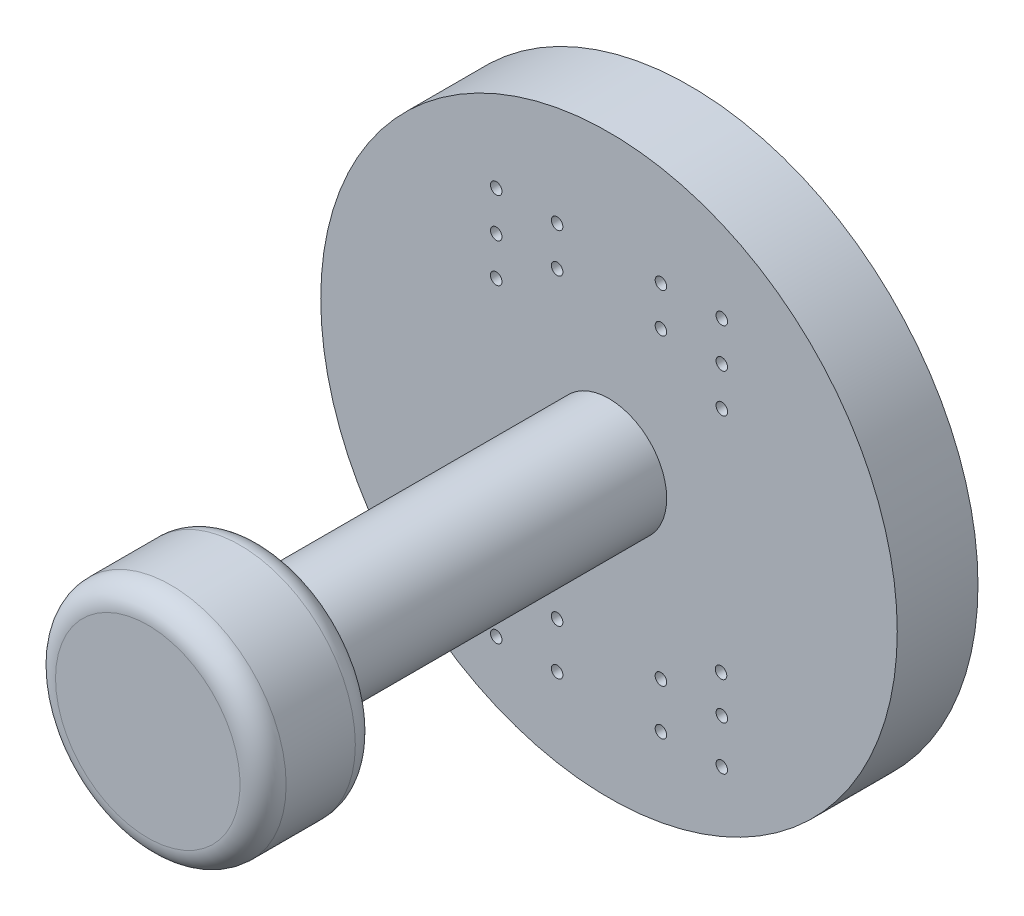
SolidWorks part; units mm, degrees
ref_plane "Front Plane" through (0, 0, 0) normal (0, 0, 1) x (1, 0, 0)
ref_plane "Top Plane" through (0, 0, 0) normal (0, 1, 0) x (1, 0, 0)
ref_plane "Right Plane" through (0, 0, 0) normal (1, 0, 0) x (0, 0, -1)
sketch "Sketch1" plane through (0, 0, 0) normal (0, 0, 1) x (1, 0, 0)
  circle A0 centre (0, 0) radius 25
  dimension "D1" = 50
extrude "Boss-Extrude1" add sketch "Sketch1" along normal blind 5
sketch "Sketch2" plane through (0, 0, 0) normal (0, 0, -1) x (-1, 0, 0)
  line L0 (0, 0) -> (0, 25) construction
  line L1 (0, 0) -> (0, -25) construction
  line L2 (-11.9711, -0.8326) -> (-14.1368, 0.4162)
  line L3 (-14.1368, 0.4162) -> (-15.5696, 8.7946)
  line L4 (-14.9974, 9.9289) -> (-9.0807, 6.1881)
  line L5 (-9.0807, 6.1881) -> (-9.0807, 4.1881)
  line L6 (0, 0) -> (-6.2363, 1.8326)
  line L7 (0.7585, 1.8326) -> (-0.7585, 1.8326)
  line L8 (-0.7585, 1.8326) -> (-0.7585, 2.3934)
  line L9 (0.7585, 1.8326) -> (0.7585, 2.3934)
  line L10 (0, 0) -> (6.2363, 1.8326)
  line L11 (11.9711, -0.8326) -> (14.1368, 0.4162)
  line L12 (9.0807, 6.1881) -> (9.0807, 4.1881)
  line L13 (14.9974, 9.9289) -> (9.0807, 6.1881)
  line L14 (14.1368, 0.4162) -> (15.5696, 8.7946)
  circle A0 centre (0, 0) radius 25 construction
  arc A1 (-11.9711, -0.8326) -> (11.9711, -0.8326) centre (0, 0) ccw
  arc A2 (-9.0807, 4.1881) -> (0, 10) centre (0, 0) cw
  arc A3 (-15.5696, 8.7946) -> (-14.9974, 9.9289) centre (-16.9766, 10.216) cw
  arc A4 (-6.2363, 1.8326) -> (6.2363, 1.8326) centre (0, -2.7478) ccw
  arc A5 (-0.7585, 2.3934) -> (0.7585, 2.3934) centre (0, 4.1881) cw
  circle A6 centre (-0.8787, 4.4971) radius 0.5181
  circle A7 centre (0.8787, 4.4971) radius 0.5181
  arc A8 (9.0807, 4.1881) -> (0, 10) centre (0, 0) ccw
  arc A9 (15.5696, 8.7946) -> (14.9974, 9.9289) centre (16.9766, 10.216) ccw
  ellipse E0 centre (-3.1163, -3.2887) end of major axis (-3.1163, -5.3887) minor radius 1.5
  ellipse E1 centre (3.1163, -3.2887) end of major axis (3.1163, -5.3887) minor radius 1.5
  point P16 (-5.3907, 8.4226)
  point P32 (-0.8806, 2.3934)
  point P33 (-0.7585, 2.3934)
  point P35 (0, 1.8326)
  point P49 (0, 6.1365)
  point P50 (0, 0)
  dimension "D1" = 12
  dimension "D2" = 10
  dimension "D7" = 2
  dimension "D10" = 9.704
  dimension "D14" = 16.9766
  dimension "D21" = 7.7377
  dimension "D25" = 1.9484
  dimension "D26" = 1.0363
  dimension "D27" = 0.8787
  dimension "D28" = 1.0363
  dimension "D29" = 1.0363
  dimension "D30" = 0.8787
  dimension "D31" = 0.8787
  dimension "D32" = 1.8601
  dimension "D3" = 7
  dimension "D4" = 8.5
  dimension "D5" = 2.5
  dimension "D6" = 2
  dimension "D8" = 230.327
  dimension "D9" = 237.697
  dimension "D11" = 57.697
  dimension "D12" = 9.0807
  dimension "D13" = 9.704
  dimension "D15" = 6.5
  dimension "D16" = 3
  dimension "D17" = 4.2
  dimension "D18" = 4.6163
  dimension "D19" = 3.1163
  dimension "D20" = 6.2363
  dimension "D22" = 6.0487
  dimension "D23" = 0.5608
  dimension "D24" = 0.7585
extrude "Boss-Extrude2" add sketch "Sketch2" along normal blind 2 contours L14 A9 L13 L12 A8 A2 L5 L4 A3 L3 L2 A1 L11 L8 A5 L9 L7 A4 L6 L10 | E0 | E1 | A7 | A6
sketch "Sketch3" plane through (0, 0, 0) normal (0, 0, -1) x (-1, 0, 0)
  line L0 (0, 0) -> (0, 25) construction
  line L1 (0, 0) -> (0, -25) construction
  circle A1 centre (0, 0) radius 25 construction
  circle A4 centre (-4.5014, 15.9102) radius 0.5
  circle A5 centre (-4.5014, 12.4971) radius 0.5
  circle A6 centre (-4.5014, -13.81) radius 0.5
  circle A7 centre (-4.5014, -17.7681) radius 0.5
  circle A10 centre (-9.7824, 15.9102) radius 0.5
  circle A11 centre (-9.7824, 12.4971) radius 0.5
  circle A12 centre (-9.7824, 9.1314) radius 0.5
  circle A13 centre (-9.7137, -10.705) radius 0.5
  circle A14 centre (-9.7837, -13.927) radius 0.5
  circle A15 centre (-9.7824, -17.7681) radius 0.5
  circle A17 centre (0, 0) radius 23.3549
  circle A18 centre (4.5014, -13.81) radius 0.5
  circle A19 centre (4.5014, -17.7681) radius 0.5
  circle A20 centre (9.7824, -17.7681) radius 0.5
  circle A21 centre (9.7837, -13.927) radius 0.5
  circle A22 centre (9.7137, -10.705) radius 0.5
  circle A23 centre (4.5014, 15.9102) radius 0.5
  circle A24 centre (4.5014, 12.4971) radius 0.5
  circle A25 centre (9.7824, 9.1314) radius 0.5
  circle A26 centre (9.7824, 12.4971) radius 0.5
  circle A27 centre (9.7824, 15.9102) radius 0.5
  point P5 (0, 0)
  point P8 (0, 0)
  point P9 (0, 0)
  point P10 (-9.7824, -10.6406)
  point P19 (0, 0)
  point P20 (0, 0)
  point P21 (-9.7837, -10.705)
  point P22 (0, 0)
  point P35 (0, 0)
  point P36 (0, 0)
  point P58 (0, 0)
  dimension "D1" = 1
  dimension "D2" = 1
  dimension "D3" = 1
  dimension "D4" = 1
  dimension "D5" = 1
  dimension "D6" = 1
  dimension "D7" = 1
  dimension "D8" = 1
  dimension "D9" = 1
  dimension "D10" = 1
  dimension "D11" = 9.7824
  dimension "D12" = 3.4132
  dimension "D13" = 9.7837
  dimension "D17" = 17.0201
  dimension "D19" = 23.3549
  dimension "D20" = 1
  dimension "D21" = 18.3294
  dimension "D22" = 20.283
  dimension "D23" = 9.7137
  dimension "D25" = 4.5014
  dimension "D26" = 13.2831
  dimension "D28" = 18.677
  dimension "D14" = 9.7824
  dimension "D15" = 4.5014
  dimension "D16" = 4.5014
  dimension "D18" = 14.5251
  dimension "D24" = 14.4552
  dimension "D27" = 4.5014
  dimension "D29" = 9.7824
  dimension "D30" = 19.5648
  dimension "D31" = 13.382
  dimension "D32" = 16.5348
extrude "Cut-Extrude1" cut sketch "Sketch3" against normal through all contours A26 | A27 | A25 | A24 | A23 | A20 | A21 | A22 | A19 | A18 | A4 | A5 | A11 | A10 | A12 | A7 | A6 | A14 | A13 | A15
sketch "Sketch4" plane through (0, 0, 0) normal (0, 0, -1) x (-1, 0, 0)
  circle A0 centre (0, 0) radius 23.0074
  circle M19 centre (0, 0) radius 25
  dimension "D1" = 46.0148
extrude "Boss-Extrude4" add sketch "Sketch4" along normal blind 2 contours A0 M19
sketch "Sketch5" plane through (0, 0, 0) normal (1, 0, 0) x (0, 0, -1)
  line L0 (0, 0) -> (-17.0912, 0) construction
  line L1 (-5, 5) -> (-35, 5)
  line L2 (-5, 25) -> (-5, -25) construction
  line L3 (-35, 5) -> (-35, 8)
  line L4 (-37, 10) -> (-43, 10)
  line L5 (-45, 8) -> (-45, 0)
  line L6 (-5, 0) -> (-45, 0)
  line L7 (-5, 5) -> (-5, 0)
  arc A0 (-43, 10) -> (-45, 8) centre (-43, 8) ccw
  arc A1 (-35, 8) -> (-37, 10) centre (-37, 8) ccw
  point P11 (-45, 4)
  point P12 (-45, 0)
  point P13 (-45, 0)
  point P14 (0, 0)
  point P17 (-45, 10)
  point P20 (-35, 10)
  dimension "D6" = 2
  dimension "D7" = 2
  dimension "D1" = 30
  dimension "D2" = 10
  dimension "D3" = 10
  dimension "D4" = 5
  dimension "D5" = 14.1421
revolve "Revolve1" add sketch "Sketch5" angle 360 about L0
